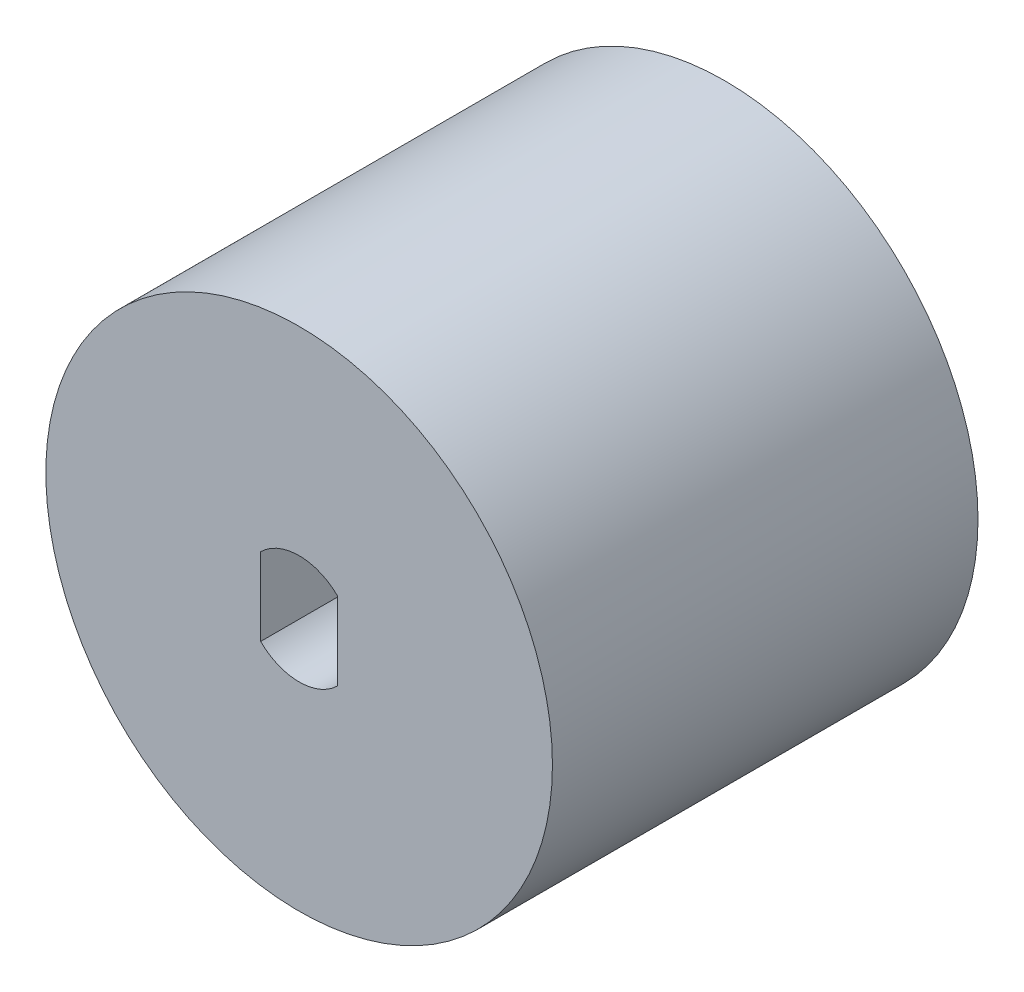
SolidWorks part; units mm, degrees
ref_plane "Front Plane" through (0, 0, 0) normal (0, 0, 1) x (1, 0, 0)
ref_plane "Top Plane" through (0, 0, 0) normal (0, 1, 0) x (1, 0, 0)
ref_plane "Right Plane" through (0, 0, 0) normal (1, 0, 0) x (0, 0, -1)
sketch "Sketch2" plane through (0, 0, 0) normal (0, 0, 1) x (1, 0, 0)
  line L2 (1.9, -1.9183) -> (1.9, 1.9183)
  line L4 (-1.9, -1.9183) -> (-1.9, 1.9183)
  line L5 (1.452, -2.2764) -> (-1.452, 2.2764) construction
  line L6 (1.452, 2.2764) -> (-1.452, -2.2764) construction
  circle A0 centre (0, 0) radius 25
  arc A1 (-1.9, -1.9183) -> (1.9, -1.9183) centre (0, 0) ccw
  circle A2 centre (0, 0) radius 1
  arc A3 (1.9, 1.9183) -> (-1.9, 1.9183) centre (0, 0) ccw
  dimension "D1" = 50
  dimension "D2" = 5.4
  dimension "D3" = 2
  dimension "D4" = 3.8
  dimension "D5" = 1.9
extrude "Boss-Extrude1" add sketch "Sketch2" against normal blind 4 contours A0 | L2 A3 L4 A1
sketch "Sketch3" plane through (0, 0, -4) normal (0, 0, -1) x (-1, 0, 0)
  circle A0 centre (0, 0) radius 25 construction
  circle A1 centre (0, 0) radius 1 construction
  circle A2 centre (0, 0) radius 25
  circle A3 centre (0, 0) radius 1
extrude "Boss-Extrude2" add sketch "Sketch3" along normal blind 2
sketch "Sketch4" plane through (0, 0, 0) normal (0, 0, 1) x (1, 0, 0)
  line L0 (0, 0) -> (0, 27.7) construction
  line L1 (0, 0) -> (0.9989, 20.9762) construction
  line L2 (0, 0) -> (-0.9989, 20.9762) construction
  line L4 (-0.8571, 18) -> (0.8571, 18)
  line L5 (0.9989, 20.9762) -> (0.8571, 18)
  line L7 (-0.8571, 18) -> (-0.9989, 20.9762)
  arc A0 (0.9989, 20.9762) -> (-0.9989, 20.9762) centre (0, 0) ccw
  dimension "D1" = 42
extrude "Cut-Extrude1" cut sketch "Sketch4" against normal through all both and the other way through all
sketch "Sketch5" plane through (0, 0, 0) normal (0, 1, 0) x (1, 0, 0)
  line L0 (0, -11.3819) -> (0, 14.3035) construction
pattern_circular "CirPattern1" count 30 over 360 about axis through (0, 0, 0) along (0, 0, 1) of "Cut-Extrude1"
sketch "Sketch6" plane through (0, 0, 0) normal (0, 0, 1) x (1, 0, 0)
  circle A0 centre (0, 0) radius 25
  circle A1 centre (0, 0) radius 12.5
  dimension "D1" = 50
  dimension "D2" = 25
extrude "Cut-Extrude2" cut sketch "Sketch6" against normal through all
sketch "Sketch7" plane through (0, 0, -6) normal (0, 0, -1) x (-1, 0, 0)
  circle A0 centre (0, 0) radius 7.5
  circle A1 centre (0, 0) radius 12.5
  circle A2 centre (0, 0) radius 12.5
  dimension "D2" = 15
  dimension "D1" = 0
extrude "Boss-Extrude3" add sketch "Sketch7" along normal blind 15
